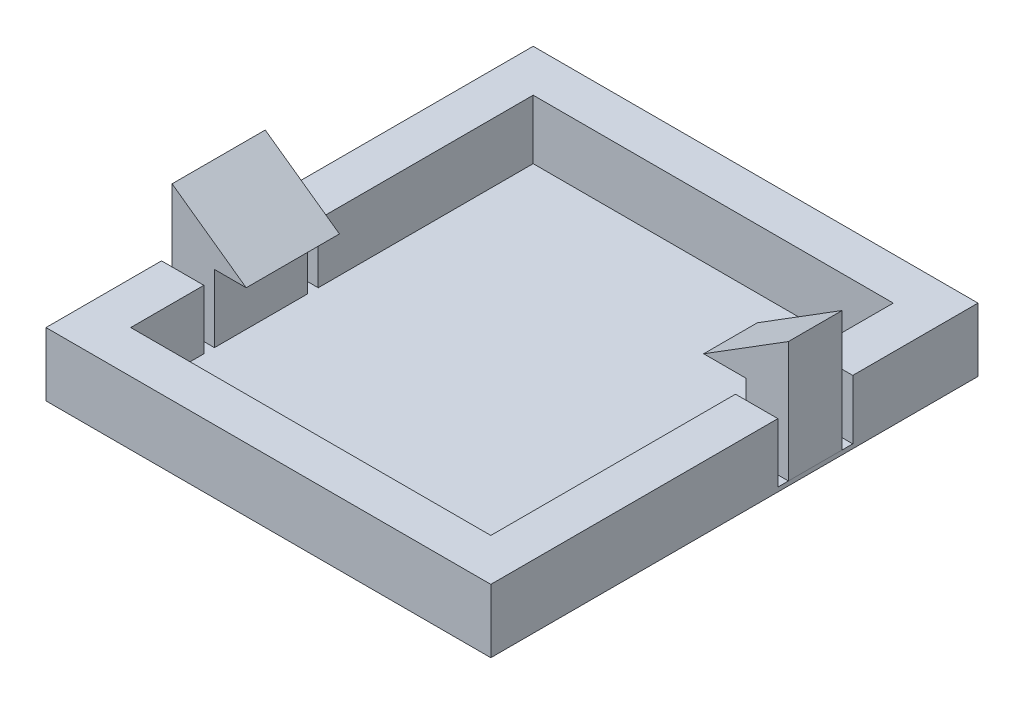
SolidWorks part; units mm, degrees
ref_plane "Front Plane" through (0, 0, 0) normal (0, 0, 1) x (1, 0, 0)
ref_plane "Top Plane" through (0, 0, 0) normal (0, 1, 0) x (1, 0, 0)
ref_plane "Right Plane" through (0, 0, 0) normal (1, 0, 0) x (0, 0, -1)
sketch "Sketch1" plane through (0, 0, 0) normal (0, 1, 0) x (1, 0, 0)
  line L0 (-10.5, -11.5) -> (-10.5, -6.0465)
  line L1 (-8.5, -9.5) -> (8.5, -9.5)
  line L2 (-8.5, -9.5) -> (-8.5, -6.0465)
  line L3 (-8.5, 9.5) -> (8.5, 9.5)
  line L4 (8.5, -9.5) -> (8.5, 2.0519)
  line L5 (-8.5, -9.5) -> (8.5, 9.5) construction
  line L6 (-8.5, 9.5) -> (8.5, -9.5) construction
  line L7 (-10.5, 11.5) -> (10.5, 11.5)
  line L8 (10.5, -11.5) -> (10.5, 2.0519)
  line L9 (-10.5, -11.5) -> (10.5, -11.5)
  line L10 (8.5, 2.0519) -> (10.5, 2.0519)
  line L13 (8.5, 5.5878) -> (10.5, 5.5878)
  line L14 (8.5, 5.5878) -> (8.5, 9.5)
  line L15 (8.5, -9.5) -> (8.5, 9.5) construction
  line L16 (10.5, 5.5878) -> (10.5, 11.5)
  line L17 (10.5, -11.5) -> (10.5, 11.5) construction
  line L18 (-10.5, -0.6476) -> (-8.5, -0.6476)
  line L19 (-10.5, -6.0465) -> (-8.5, -6.0465)
  line L20 (-10.5, -0.6476) -> (-10.5, 11.5)
  line L21 (-10.5, -11.5) -> (-10.5, 11.5) construction
  line L22 (-8.5, -0.6476) -> (-8.5, 9.5)
  line L23 (-8.5, -9.5) -> (-8.5, 9.5) construction
  point P0 (0, 0)
  dimension "D1" = 19
  dimension "D2" = 17
  dimension "D4" = 2
  dimension "D5" = 2
  dimension "D6" = 2
  dimension "D3" = 2
extrude "Boss-Extrude2" add sketch "Sketch1" along normal blind 3
sketch "Sketch4" plane through (0, 0, 0) normal (0, 1, 0) x (1, 0, 0)
  line L1 (-10.5, 11.5) -> (10.5, 11.5)
  line L2 (-10.5, 11.5) -> (-10.5, -11.5)
  line L3 (-10.5, -11.5) -> (10.5, -11.5)
  line L4 (10.5, 11.5) -> (10.5, -11.5)
  line L5 (-10.5, 11.5) -> (10.5, -11.5) construction
  line L6 (-10.5, -11.5) -> (10.5, 11.5) construction
  line L7 (10.5, -11.5) -> (10.5, 2.0519) construction
  point P4 (0, 0)
  dimension "D1" = 23
  dimension "D2" = 21
extrude "Boss-Extrude4" add sketch "Sketch4" along normal blind 0.2
sketch "Sketch6" plane through (0, 0.2, 0) normal (0, 1, 0) x (1, 0, 0)
  line L0 (-10.501, -1.1476) -> (-8.501, -1.1476)
  line L1 (-10.501, -1.1476) -> (-10.501, -5.5465)
  line L2 (-10.501, -5.5465) -> (-8.501, -5.5465)
  line L3 (-8.501, -1.1476) -> (-8.501, -5.5465)
  line L4 (-10.501, -1.1476) -> (-8.501, -5.5465) construction
  line L5 (-10.501, -5.5465) -> (-8.501, -1.1476) construction
  line L6 (10.4965, 5.0878) -> (8.4965, 5.0878)
  line L7 (10.4965, 5.0878) -> (10.4965, 2.5519)
  line L8 (10.4965, 2.5519) -> (8.4965, 2.5519)
  line L9 (8.4965, 5.0878) -> (8.4965, 2.5519)
  line L10 (10.4965, 5.0878) -> (8.4965, 2.5519) construction
  line L11 (10.4965, 2.5519) -> (8.4965, 5.0878) construction
  line L12 (-10.5, -0.6476) -> (-8.5, -0.6476) construction
  line L13 (10.5, 5.5878) -> (8.5, 5.5878) construction
  line L14 (10.5, 2.0519) -> (8.5, 2.0519) construction
  point P4 (-9.501, -3.347)
  point P9 (9.4965, 3.8199)
  dimension "D1" = 2
  dimension "D2" = 2
  dimension "D3" = 0.5
  dimension "D4" = 0.5
  dimension "D5" = 0.5
extrude "Boss-Extrude5" add sketch "Sketch6" along normal blind 3.2
sketch "Sketch7" plane through (0, 0, 5.5465) normal (0, 0, 1) x (1, 0, 0)
  line L0 (-10.501, 3.4) -> (-10.501, 5.9)
  line L1 (-10.501, 5.9) -> (-7.001, 3.4)
  line L2 (-7.001, 3.4) -> (-10.501, 3.4)
  dimension "D1" = 2.5
  dimension "D2" = 3.5
extrude "Boss-Extrude6" add sketch "Sketch7" against normal up to surface (4.3989 mm away) up to face at (-9.251, 2.2, 1.1476)
sketch "Sketch8" plane through (0, 0, -2.5519) normal (0, 0, 1) x (1, 0, 0)
  line L0 (10.4965, 3.4) -> (10.4965, 5.9)
  line L1 (10.4965, 5.9) -> (6.4965, 3.4)
  line L3 (6.4965, 3.4) -> (10.4965, 3.4)
  dimension "D1" = 2.5
  dimension "D3" = 4
extrude "Boss-Extrude7" add sketch "Sketch8" against normal up to surface (2.5359 mm away) up to face at (9.7469, 2.2, -5.0878)
